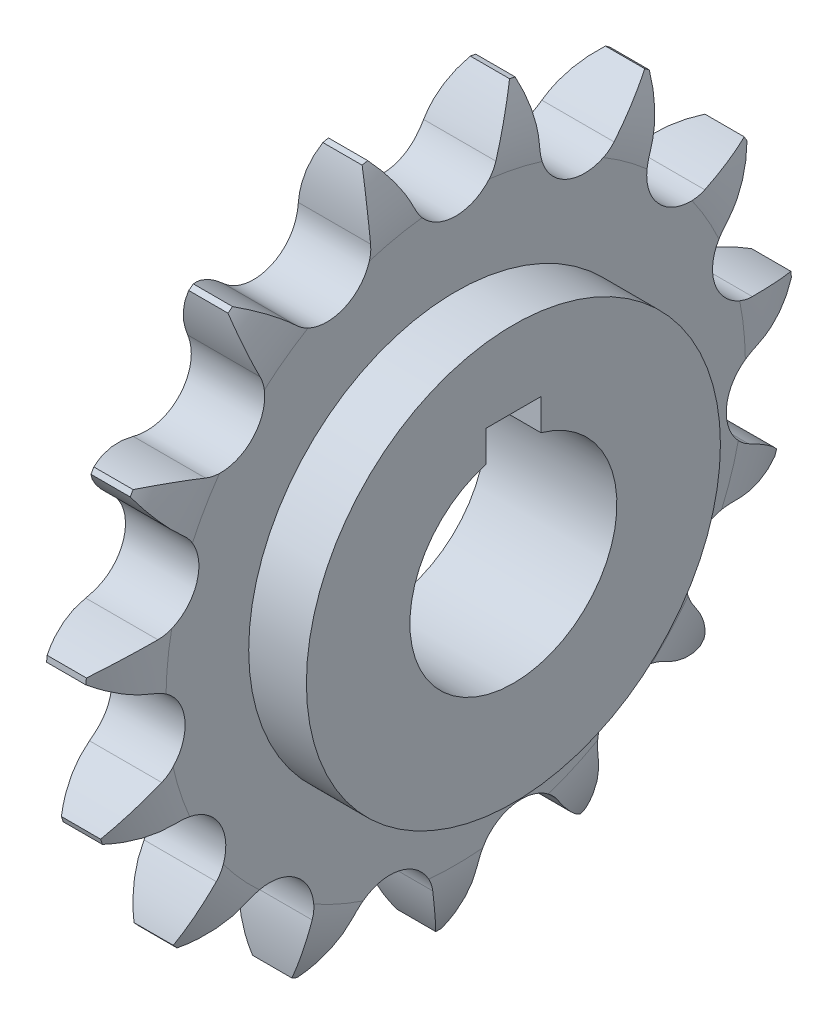
SolidWorks part; units mm, degrees
ref_plane "Plane1" through (0, 0, 0) normal (0, 0, 1) x (1, 0, 0)
ref_plane "Plane2" through (0, 0, 0) normal (0, 1, 0) x (1, 0, 0)
ref_plane "Plane3" through (0, 0, 0) normal (1, 0, 0) x (0, 0, -1)
sketch "Clipboard" plane through (0, 0, 0) normal (0, 1, 0) x (1, 0, 0)
  line L0 (0, 0) -> (9.2004, -2.4653)
  line L1 (-15, 0) -> (100, 0) construction
  line L2 (0, 0) -> (-0.8203, 0.9272)
  line L3 (0, 0) -> (-8.8973, 3.4006)
  line L4 (0, 0) -> (2.9944, 0.8023)
  line L5 (0, 0) -> (-46.8476, -17.4728)
  line L6 (0, 0) -> (-4.4098, -2.9753)
  line L7 (-0.8203, 0.9272) -> (47.2432, 14.7092)
  line L8 (-76.2, 38.1) -> (-74.4, 38.1)
  line L9 (-73.3242, 40.7328) -> (-72.926, 40.7699)
  line L10 (-73.4529, 9.1872) -> (-63.2129, 9.1872)
  circle A0 centre (0, 0) radius 3.175
  circle A1 centre (0, 0) radius 17.7306
  circle A2 centre (0, 0) radius 37.5
  dimension "Dr" = 6.35
  dimension "MHD" = 35.4612
  dimension "Hub_dia" = 75
  dimension "Num_teeth" = 15
  dimension "Pitch" = 9.525
  dimension "Width" = 3.1
  dimension "Side_relief" = 1.238
  dimension "Side_radius" = 9.525
  dimension "Overall_len" = 50
  dimension "Show_teeth" = 15
  dimension "Thickness" = 5.3196
  dimension "OAL" = 50.0005
  dimension "T_dim" = 1.8
  dimension "Fillet_rad" = 0.4
  dimension "Face_width" = 5.32
  dimension "Num_strands" = 1
  dimension "Transv_pitch" = 10.24
  dimension "Plate_wid" = 8.26
sketch "BasProSke" plane through (0, 0, 0) normal (0, 1, 0) x (1, 0, 0)
  line L0 (-10, 0) -> (60, 0) construction
  line L1 (0, 0) -> (0, 20.9886)
  line L2 (0, 0) -> (5.3196, 0)
  line L3 (5.3196, 0) -> (5.3196, 20.9886)
  line L4 (4.0816, 25.6845) -> (1.238, 25.6845)
  arc A0 (0, 20.9886) -> (1.238, 25.6845) centre (9.525, 20.9886) cw
  arc A1 (5.3196, 20.9886) -> (4.0816, 25.6845) centre (-4.2054, 20.9886) ccw
  dimension "Thickness" = 5.3196
  dimension "D1" = 9.525
  dimension "G1" = 1.238
  dimension "G2" = 1.238
  dimension "Diameter" = 51.369
revolve "Base-Revolve" add sketch "BasProSke" angle 360 about L0
sketch "TooCutSke" plane through (0, 0, 0) normal (1, 0, 0) x (0, 0, -1)
  line L0 (0, 22.9381) -> (2.9518, 21.6851) construction
  line L1 (0, 0) -> (0, 107) construction
  line L2 (0, 22.9381) -> (-10, 22.9381) construction
  line L3 (0, 22.9381) -> (-2.9518, 21.6851) construction
  arc A0 (2.9518, 21.6851) -> (5.5304, 25.5938) centre (14.876, 16.6236) cw
  arc A1 (2.9518, 21.6851) -> (-2.9518, 21.6851) centre (0, 22.9381) cw
  arc A2 (-2.9518, 21.6851) -> (-5.5304, 25.5938) centre (-14.876, 16.6236) ccw
  arc A3 (5.5304, 25.5938) -> (-5.5304, 25.5938) centre (0, 0) ccw
  dimension "R1" = 3.2067
  dimension "R2" = 12.954
  dimension "Overcut" = 26.1845
  dimension "Seat_radius" = 22.9381
  dimension "X" = 134
extrude "ToothCut" cut sketch "TooCutSke" along normal through all
pattern_circular "TeethCuts" count 15 every 24 about axis through (-10, 0, 0) along (1, 0, 0) of "ToothCut"
sketch "HubNeaOneSke" plane through (0, 0, 0) normal (-1, 0, 0) x (0, 0, 1)
  circle A0 centre (0, 0) radius 17.7306
  dimension "Diameter" = 35.4612
extrude "HubNearOne" [suppressed] add sketch "HubNeaOneSke" along normal blind 44.6809
fillet "HubNearOneFillet" [suppressed] radius 0.4
sketch "HubNeaBotSke" plane through (0, 0, 0) normal (-1, 0, 0) x (0, 0, 1)
  circle A0 centre (0, 0) radius 17.7306
  dimension "Diameter" = 35.4612
extrude "HubNearBoth" [suppressed] add sketch "HubNeaBotSke" along normal blind 22.3405
fillet "HubNearBothFillet" [suppressed] radius 0.4
ref_plane "FarPln" through (5.3196, 0, 0) normal (1, 0, 0) x (0, 0, -1)
sketch "HubFarSke" plane through (5.3196, 0, 0) normal (1, 0, 0) x (0, 0, -1)
  circle A0 centre (0, 0) radius 17.7306
  dimension "Diameter" = 35.4612
extrude "HubFar" [suppressed] add sketch "HubFarSke" along normal blind 22.3405
fillet "HubFarFillet" [suppressed] radius 0.4
sketch "BorSke" plane through (0, 0, 0) normal (1, 0, 0) x (0, 0, -1)
  circle A0 centre (0, 0) radius 5
  dimension "Diameter" = 10
extrude "Bore" cut sketch "BorSke" along normal mid plane 100.001
sketch "KeySke" plane through (0, 0, 0) normal (1, 0, 0) x (0, 0, -1)
  line L0 (-2, 0) -> (-2, 6.8)
  line L1 (-2, 6.8) -> (2, 6.8)
  line L2 (2, 6.8) -> (2, 0)
  line L3 (0, 0) -> (0, 34) construction
  line L4 (-2, 0) -> (2, 0)
  dimension "Offset" = 6.8
  dimension "Width" = 4
extrude "Keyway" [suppressed] cut sketch "KeySke" along normal mid plane 100.001
pattern_circular "Keyway2" [suppressed] count 2 every 90 about axis through (-10, 0, 0) along (1, 0, 0)
sketch "Sketch1" plane through (5.3196, 0, 0) normal (1, 0, 0) x (0, 0, -1)
  circle A0 centre (0, 0) radius 15
  circle A1 centre (0, 0) radius 7.5
  dimension "D1" = 15
  dimension "D2" = 30
extrude "Boss-Extrude1" add sketch "Sketch1" along normal offset from surface (24.6804 mm away) 30 up to face at (0, 0, -5)
sketch "Sketch3" plane through (5.3196, 0, 0) normal (1, 0, 0) x (0, 0, -1)
  circle A1 centre (0, 0) radius 7.5
  circle A2 centre (0, 0) radius 7.5
  dimension "D1" = 0
extrude "Cut-Extrude2" cut sketch "Sketch3" against normal blind 18.5
sketch "Sketch2" plane through (30, 0, 0) normal (1, 0, 0) x (0, 0, -1)
  circle A0 centre (0, 0) radius 17.7976
extrude "Cut-Extrude1" cut sketch "Sketch2" against normal blind 20.5
sketch "Sketch5" plane through (9.5, 0, 0) normal (1, 0, 0) x (0, 0, -1)
  line L0 (-2, 9.5) -> (-2, 5.5)
  line L1 (-2, 9.5) -> (2, 9.5)
  line L2 (-2, 5.5) -> (2, 5.5)
  line L3 (2, 9.5) -> (2, 5.5)
  line L4 (-2, 9.5) -> (2, 5.5) construction
  line L5 (-2, 5.5) -> (2, 9.5) construction
  line L6 (0, 7.5) -> (0, 0) construction
  circle A0 centre (0, 0) radius 7.5 construction
  point P1 (0, 7.5)
  dimension "D1" = 4
extrude "Cut-Extrude5" cut sketch "Sketch5" against normal through all
equation "' \"Pitch@Clipboard\" = 12.7"
equation "' \"Num_strands@Clipboard\" = 1"
equation "' \"Num_teeth@Clipboard\" = 9"
equation "' \"Hub_dia@Clipboard\" = 50"
equation "' \"Overall_len@Clipboard\" = 3"
equation "' \"Diameter@BorSke\" = 12"
equation "' \"T_dim@Clipboard\" = 1"
equation "' \"Width@KeySke\" = 2"
equation "' \"Dr@Clipboard\" = 8.51"
equation "' \"Face_width@Clipboard\" = 7.2"
equation "' \"Side_radius@Clipboard\" = 12.7"
equation "' \"Side_relief@Clipboard\" = 1.27"
equation "' \"Transv_pitch@Clipboard\" = 13.92"
equation "' \"Show_teeth@Clipboard\" = 9"
equation "' \"Fillet_rad@Clipboard\" = 0.6"
equation "' \"Plate_wid@Clipboard\" = 11.8"
equation "\"Num_teeth@Clipboard\" = int( \"Num_teeth@Clipboard\" )"
equation "\"Num_teeth@Clipboard\" = ((sgn( \"Num_teeth@Clipboard\" - 5.0)+1)*( \"Num_teeth@Clipboard\" - 5.0))/2 +5.0"
equation "\"Num_teeth@Clipboard\" = ((sgn( \"Num_teeth@Clipboard\" - 200.0)-1)*( \"Num_teeth@Clipboard\" - 200.0))/-2 +200.0"
equation "\"MHD@Clipboard\" = \"Pitch@Clipboard\" * (1.0 / tan(3.14159265 / \"Num_teeth@Clipboard\" )) - 1.04 * \"Plate_wid@Clipboard\" - 0.76"
equation "\"Thickness@Clipboard\"  = \"Face_width@Clipboard\" + (\"Num_strands@Clipboard\" - 1) * \"Transv_pitch@Clipboard\""
equation "\"OAL@Clipboard\" = \"Thickness@Clipboard\" + 2 * \"Fillet_rad@Clipboard\" + 1"
equation "\"MHD@Clipboard\" = ((sgn( \"MHD@Clipboard\" - \"Hub_dia@Clipboard\" )-1)*( \"MHD@Clipboard\" - \"Hub_dia@Clipboard\" ))/-2+ \"Hub_dia@Clipboard\""
equation "\"OAL@Clipboard\" = ((sgn( \"OAL@Clipboard\" - \"Overall_len@Clipboard\" )+1)*( \"OAL@Clipboard\" - \"Overall_len@Clipboard\" ))/2 + \"Overall_len@Clipboard\" + 0.0005"
equation "\"Num_teeth@TeethCuts\" = int( \"Show_teeth@Clipboard\" ) + 1"
equation "\"Num_teeth@TeethCuts\" = ((sgn( \"Num_teeth@TeethCuts\" - \"Num_teeth@Clipboard\" )-1)*( \"Num_teeth@TeethCuts\" - \"Num_teeth@Clipboard\" ))/-2+ \"Num_teeth@Clipboard\""
equation "\"Num_teeth@TeethCuts\" = ((sgn( \"Num_teeth@TeethCuts\" - 2.0)+1)*( \"Num_teeth@TeethCuts\" - 2.0))/2 +2.0"
equation "\"Angle@TeethCuts\" = 360.0 / \"Num_teeth@Clipboard\""
equation "\"Seat_radius@TooCutSke\" = ( \"Pitch@Clipboard\" / 2.0) / sin(3.14159265 / \"Num_teeth@Clipboard\" ) - \"Dr@Clipboard\" / 2.0 + \"Dr@Clipboard\" * 0.505"
equation "\"R1@TooCutSke\"  = \"Dr@Clipboard\" * 0.505"
equation "\"X@TooCutSke\" = 140.0 - (90.0 / \"Num_teeth@Clipboard\")"
equation "\"R2@TooCutSke\" = 0.12 * \"Dr@Clipboard\" * ( \"Num_teeth@Clipboard\" + 2.0)"
equation "\"Overcut@TooCutSke\" = 0.5 + 0.625 * \"Pitch@Clipboard\" - 0.5 * \"Dr@Clipboard\"  +  \"Pitch@Clipboard\" / 2.0 / sin(3.14159265 / \"Num_teeth@Clipboard\" )"
equation "\"Diameter@BasProSke\" = 2.0 * ( 0.625 * \"Pitch@Clipboard\" - 0.5 * \"Dr@Clipboard\"  +  \"Pitch@Clipboard\" / 2.0 / sin(3.14159265 / \"Num_teeth@Clipboard\" ))"
equation "\"Thickness@BasProSke\"  = \"Thickness@Clipboard\""
equation "\"G1@BasProSke\" =  \"Side_relief@Clipboard\""
equation "\"G2@BasProSke\" =  \"Side_relief@Clipboard\""
equation "\"D1@BasProSke\" =  \"Side_radius@Clipboard\""
equation "\"Diameter@HubNeaOneSke\" = \"MHD@Clipboard\""
equation "\"Length@HubNearOne\" = \"OAL@Clipboard\" - \"Thickness@BasProSke\""
equation "\"Diameter@HubNeaBotSke\" = \"MHD@Clipboard\""
equation "\"Length@HubNearBoth\" = ( \"OAL@Clipboard\" - \"Thickness@BasProSke\" ) / 2.0"
equation "\"D1@HubNearOneFillet\" = \"Fillet_rad@Clipboard\""
equation "\"D1@HubNearBothFillet\" = \"Fillet_rad@Clipboard\""
equation "\"Thickness@FarPln\" = \"Thickness@BasProSke\""
equation "\"Diameter@HubFarSke\" = \"MHD@Clipboard\""
equation "\"Length@HubFar\" = ( \"OAL@Clipboard\" - \"Thickness@BasProSke\" ) / 2.0"
equation "\"D1@HubFarFillet\" = \"Fillet_rad@Clipboard\""
equation "\"D1@Bore\" = \"OAL@Clipboard\" * 2.0"
equation "\"D1@Keyway\" = \"OAL@Clipboard\" * 2.0"
equation "\"Offset@KeySke\" = \"T_dim@Clipboard\" + \"Diameter@BorSke\" / 2.0"
